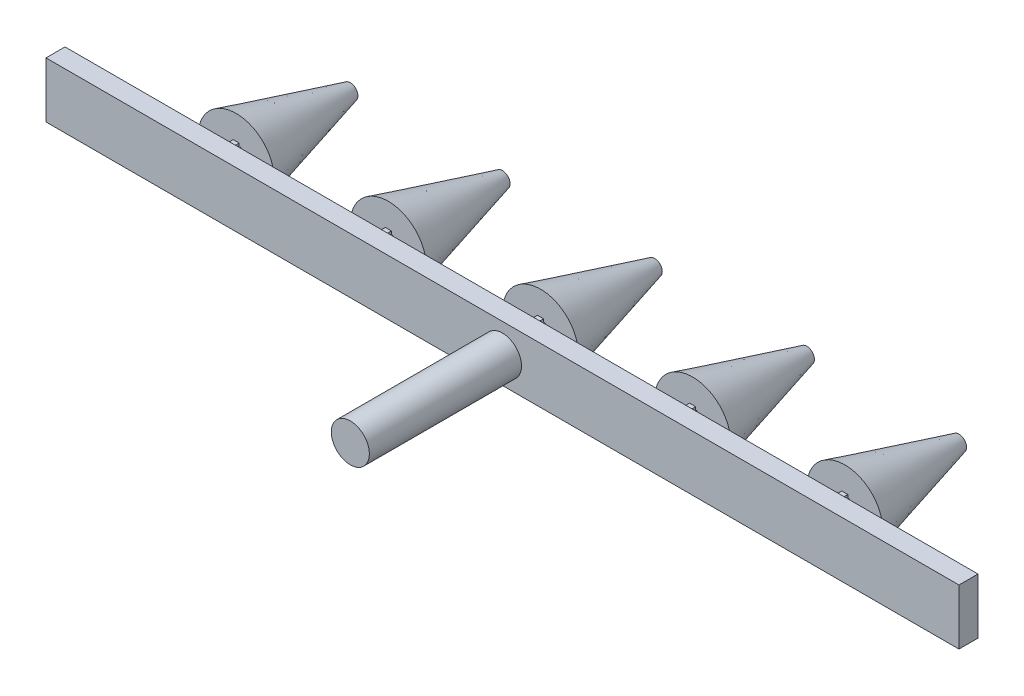
SolidWorks part; units mm, degrees
ref_plane "Front Plane" through (0, 0, 0) normal (0, 0, 1) x (1, 0, 0)
ref_plane "Top Plane" through (0, 0, 0) normal (0, 1, 0) x (1, 0, 0)
ref_plane "Right Plane" through (0, 0, 0) normal (1, 0, 0) x (0, 0, -1)
sketch "Sketch1" plane through (0, 0, 0) normal (0, 0, 1) x (1, 0, 0)
  line L0 (0, 120) -> (-62.0404, 120) construction
  line L3 (4, 18) -> (-4, 18)
  line L5 (204, 18) -> (196, 18)
  line L6 (196, 14.4568) -> (196, 18)
  line L7 (-4, 14.4568) -> (-4, 18)
  line L8 (204, 14.4568) -> (204, 18)
  line L9 (404, 18) -> (396, 18)
  line L10 (4, 14.4568) -> (4, 18)
  line L11 (396, 14.4568) -> (396, 18)
  line L12 (404, 14.4568) -> (404, 18)
  line L13 (604, 18) -> (596, 18)
  line L14 (596, 14.4568) -> (596, 18)
  line L15 (604, 14.4568) -> (604, 18)
  line L16 (804, 18) -> (796, 18)
  line L17 (796, 14.4568) -> (796, 18)
  line L18 (804, 14.4568) -> (804, 18)
  arc A0 (-4, 14.4568) -> (4, 14.4568) centre (0, 0) ccw
  arc A1 (196, 14.4568) -> (204, 14.4568) centre (200, 0) ccw
  arc A2 (396, 14.4568) -> (404, 14.4568) centre (400, 0) ccw
  arc A3 (596, 14.4568) -> (604, 14.4568) centre (600, 0) ccw
  arc A4 (796, 14.4568) -> (804, 14.4568) centre (800, 0) ccw
  dimension "D1" = 30
  dimension "D2" = 120
  dimension "D3" = 8
  dimension "D4" = 5
extrude "Boss-Extrude1" add sketch "Sketch1" against normal blind 25
sketch "Sketch2" plane through (0, 0, 0) normal (1, 0, 0) x (0, 0, -1)
  line L0 (25, -0.2716) -> (175, -0.2716)
  line L1 (25, -15) -> (25, 14.4568) construction
  line L2 (175, -0.2716) -> (175, 9.7284)
  line L3 (175, 9.7284) -> (25, 49.7284)
  line L4 (25, 49.7284) -> (25, -0.2716)
  dimension "D1" = 150
  dimension "D2" = 50
  dimension "D3" = 10
revolve "Revolve1" add sketch "Sketch2" angle 360 about L0
sketch "Sketch3" plane through (0, 0, -175) normal (0, 0, -1) x (-1, 0, 0)
  circle A0 centre (0, 0) radius 6
  dimension "D1" = 12
extrude "Cut-Extrude1" cut sketch "Sketch3" against normal up to surface (150 mm away) up to face at (0, 8.8642, -25)
sketch "Sketch4" plane through (0, 0, -175) normal (0, 0, -1) x (-1, 0, 0)
  point P0 (0, -0.2716)
sketch "Sketch5" plane through (0, 0, 0) normal (1, 0, 0) x (0, 0, -1)
  line L0 (0, 0) -> (175, -0.2716) construction
  line L1 (0, 366.024) -> (0, -406.5721) construction
  line L2 (0, 59.7615) -> (175, 59.7615) construction
  line L6 (153.6975, -0.2385) -> (153.6975, 59.7615) construction
  dimension "D1" = 60
ref_plane "Plane2" through (200, 0, 0) normal (1, 0, 0) x (0, 0, -1)
ref_plane "Plane3" through (400, 0, 0) normal (1, 0, 0) x (0, 0, -1)
ref_plane "Plane4" through (600, 0, 0) normal (1, 0, 0) x (0, 0, -1)
ref_plane "Plane5" through (800, 0, 0) normal (1, 0, 0) x (0, 0, -1)
sketch "Sketch7" plane through (200, 0, 0) normal (1, 0, 0) x (0, 0, -1)
  line L4 (25, -0.2716) -> (175, -0.2716)
  line L5 (175, -0.2716) -> (175, 9.7284)
  line L6 (175, 9.7284) -> (25, 49.7284)
  line L7 (25, 49.7284) -> (25, -0.2716)
  line L8 (25, -0.2716) -> (175, -0.2716)
  line L9 (175, -0.2716) -> (175, 9.7284)
  line L10 (175, 9.7284) -> (25, 49.7284)
  line L11 (25, 49.7284) -> (25, -0.2716)
  dimension "D1" = 0
revolve "Revolve2" add sketch "Sketch7" angle 360 about L8
sketch "Sketch8" plane through (400, 0, 0) normal (1, 0, 0) x (0, 0, -1)
  line L4 (25, -0.2716) -> (175, -0.2716)
  line L5 (175, -0.2716) -> (175, 9.7284)
  line L6 (175, 9.7284) -> (25, 49.7284)
  line L7 (25, 49.7284) -> (25, -0.2716)
  line L8 (25, -0.2716) -> (175, -0.2716)
  line L9 (175, -0.2716) -> (175, 9.7284)
  line L10 (175, 9.7284) -> (25, 49.7284)
  line L11 (25, 49.7284) -> (25, -0.2716)
  dimension "D1" = 0
revolve "Revolve3" add sketch "Sketch8" angle 360 about L8
sketch "Sketch9" plane through (600, 0, 0) normal (1, 0, 0) x (0, 0, -1)
  line L4 (25, -0.2716) -> (175, -0.2716)
  line L5 (175, -0.2716) -> (175, 9.7284)
  line L6 (175, 9.7284) -> (25, 49.7284)
  line L7 (25, 49.7284) -> (25, -0.2716)
  line L8 (25, -0.2716) -> (175, -0.2716)
  line L9 (175, -0.2716) -> (175, 9.7284)
  line L10 (175, 9.7284) -> (25, 49.7284)
  line L11 (25, 49.7284) -> (25, -0.2716)
  dimension "D1" = 0
revolve "Revolve4" add sketch "Sketch9" angle 360 about L8
sketch "Sketch10" plane through (800, 0, 0) normal (1, 0, 0) x (0, 0, -1)
  line L4 (25, -0.2716) -> (175, -0.2716)
  line L5 (175, -0.2716) -> (175, 9.7284)
  line L6 (175, 9.7284) -> (25, 49.7284)
  line L7 (25, 49.7284) -> (25, -0.2716)
  line L8 (25, -0.2716) -> (175, -0.2716)
  line L9 (175, -0.2716) -> (175, 9.7284)
  line L10 (175, 9.7284) -> (25, 49.7284)
  line L11 (25, 49.7284) -> (25, -0.2716)
  dimension "D1" = 0
revolve "Revolve5" add sketch "Sketch10" angle 360 about L8
sketch "Sketch11" plane through (0, 0, -175) normal (0, 0, -1) x (-1, 0, 0)
  circle A0 centre (-200, -0.2716) radius 6
  circle A1 centre (-200, -0.2716) radius 10
  circle A2 centre (-200, -0.2716) radius 10
  circle A3 centre (0, 0) radius 6
  circle A4 centre (0, 0) radius 6
  circle A5 centre (-400, -0.2716) radius 6
  circle A6 centre (-600, -0.2716) radius 6
  circle A7 centre (-800, -0.2716) radius 6
  dimension "D3" = 12
  dimension "D1" = 0
  dimension "D2" = 0
  dimension "D4" = 4
extrude "Cut-Extrude2" cut sketch "Sketch11" against normal blind 150
ref_plane "Plane6" through (1000, 0, 0) normal (1, 0, 0) x (0, 0, -1)
sketch "Sketch12" plane through (1000, 0, 0) normal (1, 0, 0) x (0, 0, -1)
  line L0 (25, 18) -> (0, 18) construction
  line L1 (0, -35) -> (-25, -35)
  line L2 (0, -35) -> (0, 38)
  line L3 (0, 38) -> (-25, 38)
  line L4 (-25, -35) -> (-25, 38)
  line L5 (0, -15) -> (25, -15) construction
  line L6 (0, 14.4568) -> (0, -15) construction
  dimension "D1" = 20
  dimension "D2" = 20
  dimension "D3" = 25
extrude "Boss-Extrude2" add sketch "Sketch12" against normal blind 1200
sketch "Sketch13" plane through (0, 0, 25) normal (0, 0, 1) x (1, 0, 0)
  circle A0 centre (400, -0.2716) radius 25
  dimension "D1" = 50
extrude "Boss-Extrude3" add sketch "Sketch13" along normal blind 200
scale "Scale1" scale about centroid uniform scaling yes scale factor 0.6
sketch "Sketch14" plane through (0, 0, 0) normal (0, 1, 0) x (1, 0, 0)
  line L0 (400.2107, 21.9981) -> (400.2107, -833.0019) construction
  line L1 (402.6107, 21.9981) -> (397.8107, 21.9981) construction
  line L2 (400.2107, 21.9981) -> (400.2107, 111.9981) construction
  line L3 (406.2107, 111.9981) -> (394.2107, 111.9981) construction
  dimension "D1" = 855
